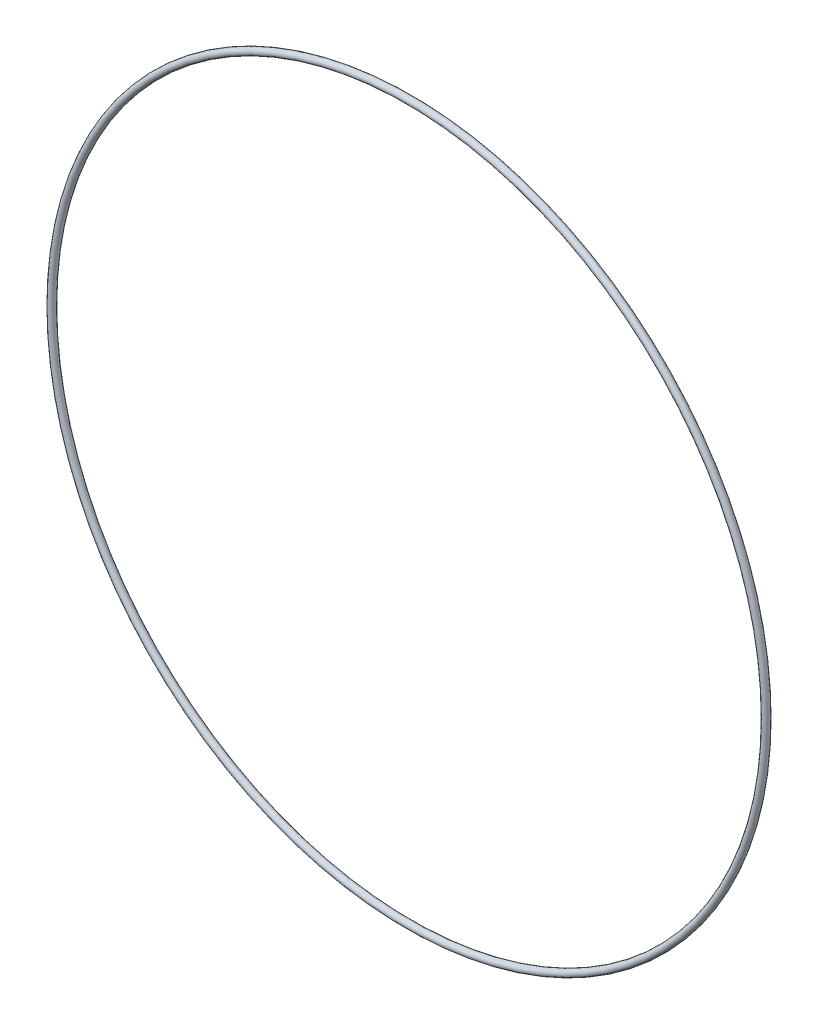
SolidWorks part; units mm, degrees
material "O-Ring (NBR)"
ref_plane "Front Plane" through (0, 0, 0) normal (0, 0, 1) x (1, 0, 0)
ref_plane "Top Plane" through (0, 0, 0) normal (0, 1, 0) x (1, 0, 0)
ref_plane "Right Plane" through (0, 0, 0) normal (1, 0, 0) x (0, 0, -1)
sketch "Sketch1" plane through (0, 0, 0) normal (0, 0, 1) x (1, 0, 0)
  circle A0 centre (0, 0) radius 154
  dimension "D1" = 308
sketch "Sketch2" plane through (0, 0, 0) normal (0, 1, 0) x (1, 0, 0)
  circle A0 centre (154, 0) radius 1.5
  dimension "D1" = 3
sweep "Sweep1" add profiles "Sketch2" path "Sketch1"
sketch "Sketch3" plane through (0, 0, 0) normal (0, 0, 1) x (1, 0, 0)
  line L0 (-163.5, 70.7219) -> (-163.5, -71.1098)
  line L1 (-124.694, -92.2504) -> (-153.1235, -84.6327)
  line L2 (-119, -93) -> (119, -93)
  line L3 (124.694, -92.2504) -> (153.1235, -84.6327)
  line L4 (163.5, -71.1098) -> (163.5, 70.7219)
  line L5 (153.1235, 84.2449) -> (82.194, 103.2504)
  line L6 (76.5, 104) -> (-76.5, 104)
  line L7 (-82.194, 103.2504) -> (-153.1235, 84.2449)
  line L8 (-161.5, 70.7219) -> (-161.5, -71.1098) construction
  line L9 (-124.1764, -90.3185) -> (-152.6058, -82.7009) construction
  line L10 (-119, -91) -> (119, -91) construction
  line L11 (124.1764, -90.3185) -> (152.6058, -82.7009) construction
  line L12 (161.5, -71.1098) -> (161.5, 70.7219) construction
  line L13 (152.6058, 82.313) -> (81.6764, 101.3185) construction
  line L14 (76.5, 102) -> (-76.5, 102) construction
  line L15 (-81.6764, 101.3185) -> (-152.6058, 82.313) construction
  line L16 (0, 0) -> (0, 80.8457) construction
  line L17 (0, 0) -> (192.9468, 0) construction
  arc A0 (-161.5, 70.7219) -> (-152.6058, 82.313) centre (-149.5, 70.7219) cw construction
  arc A1 (161.5, 70.7219) -> (152.6058, 82.313) centre (149.5, 70.7219) ccw construction
  arc A2 (-153.1235, -84.6327) -> (-163.5, -71.1098) centre (-149.5, -71.1098) cw
  arc A3 (-124.694, -92.2504) -> (-119, -93) centre (-119, -71) ccw
  arc A4 (124.694, -92.2504) -> (119, -93) centre (119, -71) cw
  arc A5 (153.1235, -84.6327) -> (163.5, -71.1098) centre (149.5, -71.1098) ccw
  arc A6 (163.5, 70.7219) -> (153.1235, 84.2449) centre (149.5, 70.7219) ccw
  arc A7 (76.5, 104) -> (82.194, 103.2504) centre (76.5, 82) cw
  arc A8 (-82.194, 103.2504) -> (-76.5, 104) centre (-76.5, 82) cw
  arc A9 (-163.5, 70.7219) -> (-153.1235, 84.2449) centre (-149.5, 70.7219) cw
  arc A10 (-152.6058, -82.7009) -> (-161.5, -71.1098) centre (-149.5, -71.1098) cw construction
  arc A11 (-124.1764, -90.3185) -> (-119, -91) centre (-119, -71) ccw construction
  arc A12 (124.1764, -90.3185) -> (119, -91) centre (119, -71) cw construction
  arc A13 (152.6058, -82.7009) -> (161.5, -71.1098) centre (149.5, -71.1098) ccw construction
  arc A14 (76.5, 102) -> (81.6764, 101.3185) centre (76.5, 82) cw construction
  arc A15 (-81.6764, 101.3185) -> (-76.5, 102) centre (-76.5, 82) cw construction
  dimension "D3" = 12
  dimension "D5" = 20
  dimension "D6" = 20
  dimension "D7" = 12
  dimension "D1" = 102
  dimension "D2" = 193
  dimension "D4" = 15
  dimension "D8" = 238
  dimension "D9" = 15
  dimension "D10" = 153
  dimension "D11" = 323
  dimension "D12" = 2
sketch "Sketch4" plane through (0, 0, 0) normal (0, 1, 0) x (1, 0, 0)
  circle A0 centre (163.5, 0) radius 1.5
  dimension "D1" = 3
sweep "Sweep2" [suppressed] add profiles "Sketch4" path "Sketch3"
